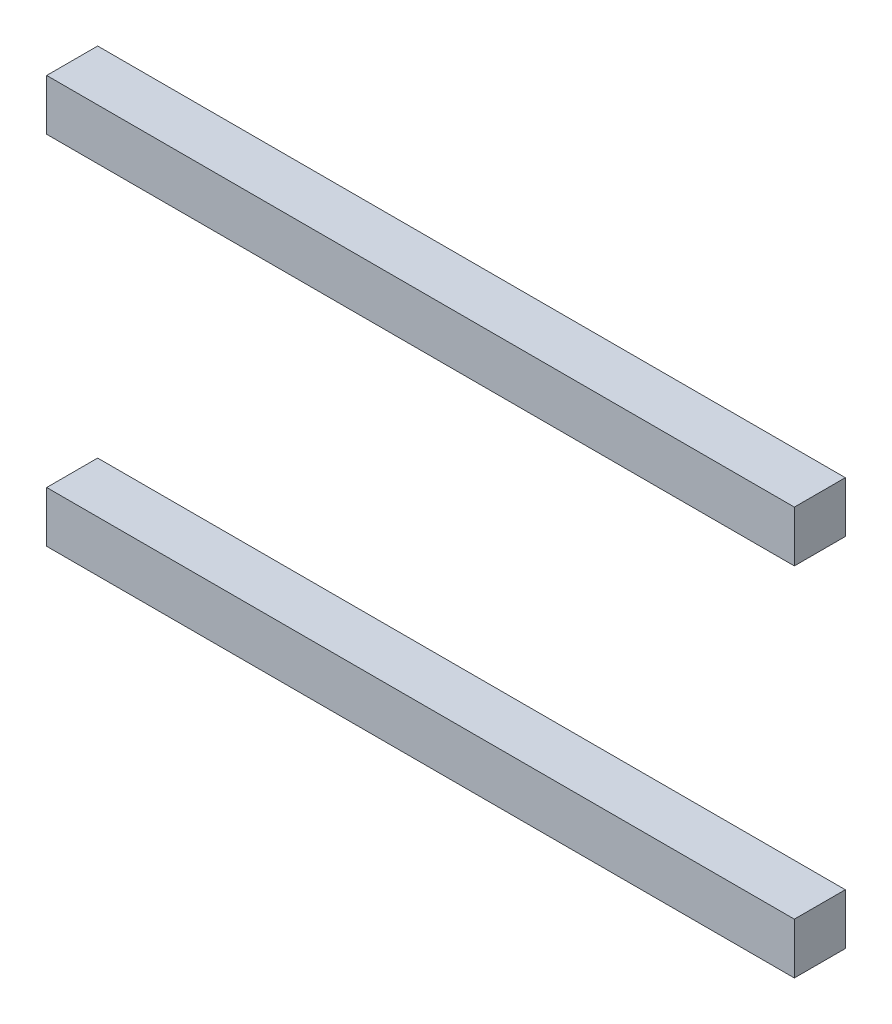
SolidWorks part; units mm, degrees
ref_plane "前视基准面" through (0, 0, 0) normal (0, 0, 1) x (1, 0, 0)
ref_plane "上视基准面" through (0, 0, 0) normal (0, 1, 0) x (1, 0, 0)
ref_plane "右视基准面" through (0, 0, 0) normal (1, 0, 0) x (0, 0, -1)
other "Configuration Table"
sketch "草图1" plane through (0, 0, 0) normal (0, 0, 1) x (1, 0, 0)
  line L1 (-165.6081, 92.3649) -> (274.3919, 92.3649)
  line L2 (-165.6081, 92.3649) -> (-165.6081, 62.3649)
  line L3 (-165.6081, 62.3649) -> (274.3919, 62.3649)
  line L4 (274.3919, 92.3649) -> (274.3919, 62.3649)
  line L5 (-165.6081, -117.6351) -> (274.3919, -117.6351)
  line L6 (-165.6081, -117.6351) -> (-165.6081, -147.6351)
  line L7 (-165.6081, -147.6351) -> (274.3919, -147.6351)
  line L8 (274.3919, -117.6351) -> (274.3919, -147.6351)
  dimension "D1" = 440
  dimension "D2" = 30
  dimension "D3" = 180
extrude "凸台-拉伸1" add sketch "草图1" along normal blind 30
